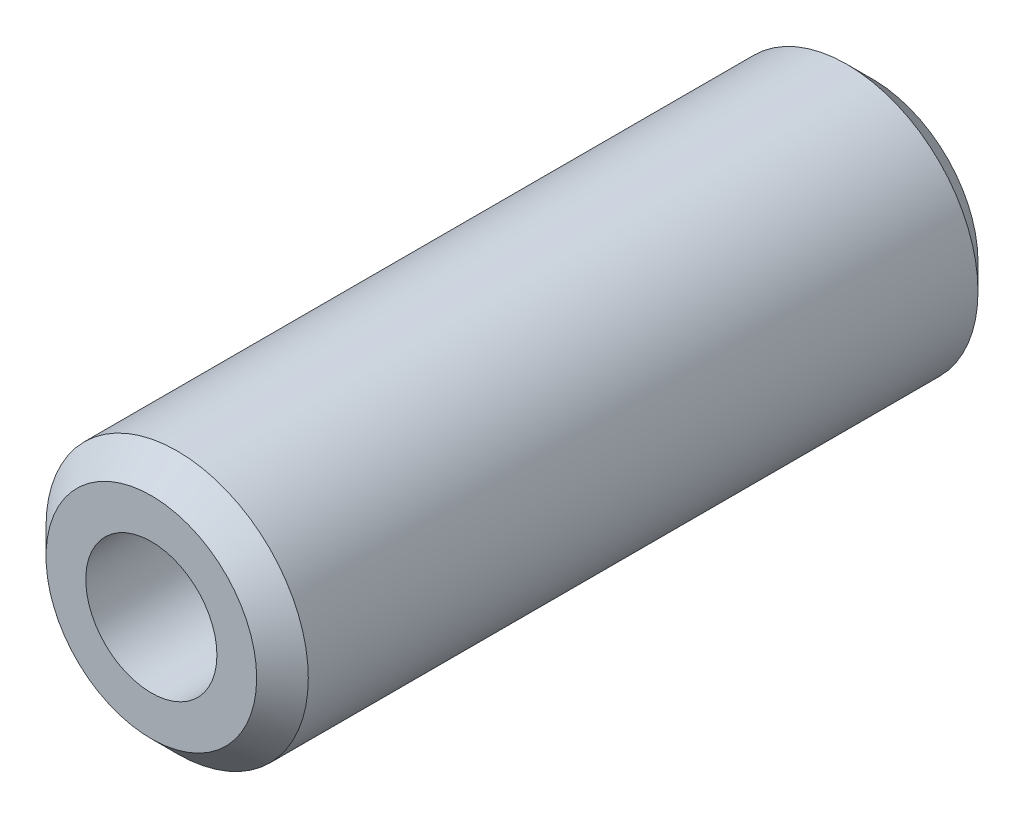
SolidWorks part; units mm, degrees
ref_plane "Front Plane" through (0, 0, 0) normal (0, 0, 1) x (1, 0, 0)
ref_plane "Top Plane" through (0, 0, 0) normal (0, 1, 0) x (1, 0, 0)
ref_plane "Right Plane" through (0, 0, 0) normal (1, 0, 0) x (0, 0, -1)
sketch "Sketch1" plane through (0, 0, 0) normal (0, 0, 1) x (1, 0, 0)
  circle A0 centre (0, 0) radius 12.7
  circle A1 centre (0, 0) radius 6.35
  dimension "D1" = 12.7
  dimension "D2" = 25.4
extrude "Boss-Extrude1" add sketch "Sketch1" along normal mid plane 69.85
chamfer "Chamfer1" distance 2.5 angle 45 2 edges at (12.7, 0, -34.925) (12.7, 0, 34.925)
